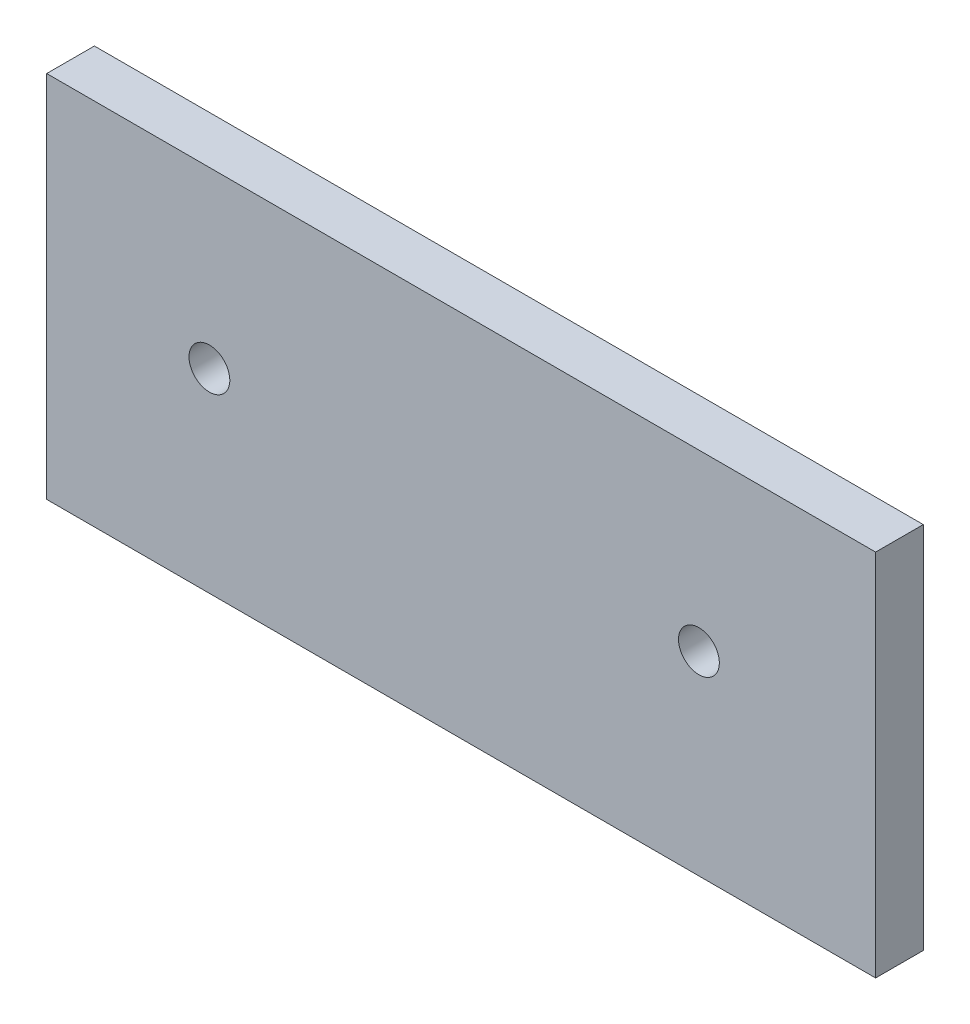
SolidWorks part; units mm, degrees
ref_plane "Front Plane" through (0, 0, 0) normal (0, 0, 1) x (1, 0, 0)
ref_plane "Top Plane" through (0, 0, 0) normal (0, 1, 0) x (1, 0, 0)
ref_plane "Right Plane" through (0, 0, 0) normal (1, 0, 0) x (0, 0, -1)
sketch "Sketch1" plane through (0, 0, 0) normal (0, 0, 1) x (1, 0, 0)
  line L1 (-101.6, 0) -> (0, 0)
  line L2 (-101.6, 0) -> (-101.6, 45.212)
  line L3 (-101.6, 45.212) -> (0, 45.212)
  line L4 (0, 0) -> (0, 45.212)
extrude "Boss-Extrude1" add sketch "Sketch1" along normal blind 5.842
hole_wizard "M6x1.0 Tapped Hole1" positions "Sketch2" profile "Sketch3" tap size "M6x1.0" standard "ANSI Metric"
sketch "Sketch2" plane through (-50.8, -38.1, 0) normal (0, 0, -1) x (-1, 0, 0)
  line L0 (-29.143, 61.9649) -> (30.8599, 61.9649) construction
  line L1 (0, 76.452) -> (0, 39.5098) construction
  point P0 (-29.143, 61.9649)
  point P1 (30.8599, 61.9649)
sketch "Sketch3" plane through (-21.657, 23.8649, 0) normal (1, 0, 0) x (0, 1, 0)
  line L0 (0, 0) -> (0, 16.4882)
  line L1 (0, 16.4882) -> (2.5, 14.986)
  line L2 (2.5, 14.986) -> (2.5, 0)
  line L3 (2.5, 0) -> (0, 0)
  line L4 (0, 16.4882) -> (-2.5, 14.986) construction
  line L5 (0, -6.35) -> (0, 107.95) construction
  dimension "Tap Drill Dia." = 5
  dimension "Tap Drill Depth" = 14.986
  dimension "Drill Angle" = 118
cosmetic thread "Hole Thread1" parameters "D1"=5.842, "D2"=6
cosmetic thread "Hole Thread2" parameters "D1"=5.842, "D2"=6
